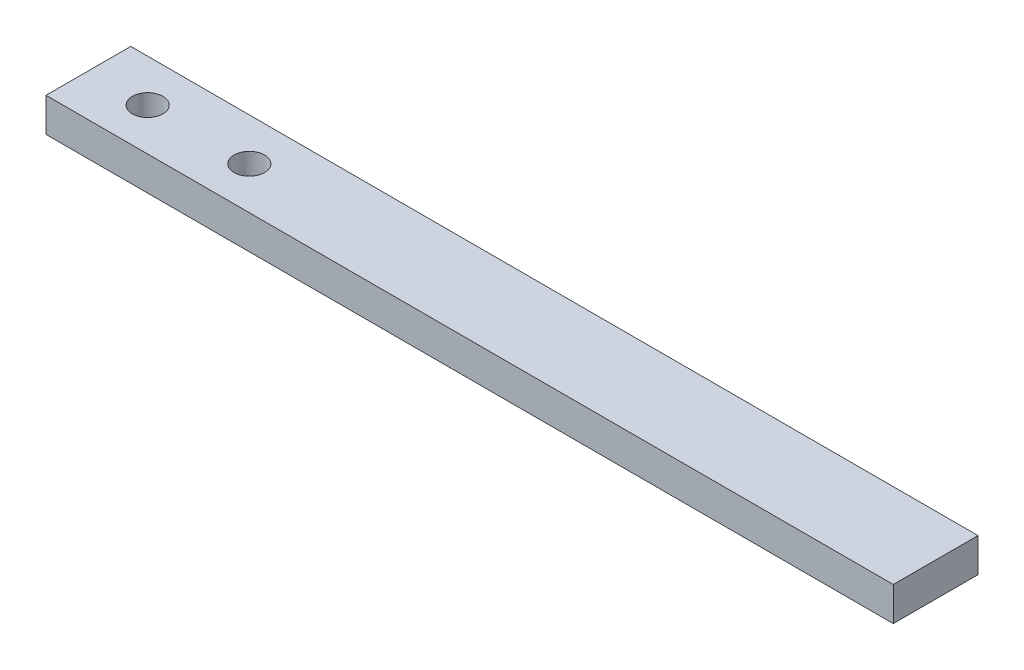
SolidWorks part; units mm, degrees
ref_plane "前视基准面" through (0, 0, 0) normal (0, 0, 1) x (1, 0, 0)
ref_plane "上视基准面" through (0, 0, 0) normal (0, 1, 0) x (1, 0, 0)
ref_plane "右视基准面" through (0, 0, 0) normal (1, 0, 0) x (0, 0, -1)
sketch "草图1" plane through (0, 0, 0) normal (0, 1, 0) x (1, 0, 0)
  line L0 (-4.1827, -1.5573) -> (45.8173, -1.5573)
  line L1 (-4.1827, 3.4427) -> (45.8173, 3.4427)
  line L2 (-4.1827, 3.4427) -> (-4.1827, -1.5573)
  line L3 (45.8173, 3.4427) -> (45.8173, -1.5573)
  dimension "D1" = 5
  dimension "D2" = 50
extrude "凸台-拉伸1" add sketch "草图1" along normal blind 2 contours L1 L3 L0 L2
sketch "草图2" plane through (0, 2, 0) normal (0, 1, 0) x (1, 0, 0)
  line L0 (-4.1827, 0.9427) -> (45.8173, 0.9427) construction
  line L1 (-4.1827, 3.4427) -> (-4.1827, -1.5573) construction
  line L2 (45.8173, 3.4427) -> (45.8173, -1.5573) construction
  circle A0 centre (-0.6827, 0.9427) radius 0.9
  circle A1 centre (5.3173, 0.9427) radius 0.9
  point P0 (-0.6827, 0.9427)
  point P1 (5.3173, 0.9427)
  dimension "D3" = 1.8
  dimension "D4" = 1.8
  dimension "D1" = 3.5
  dimension "D2" = 6
extrude "切除-拉伸1" cut sketch "草图2" against normal blind 2
